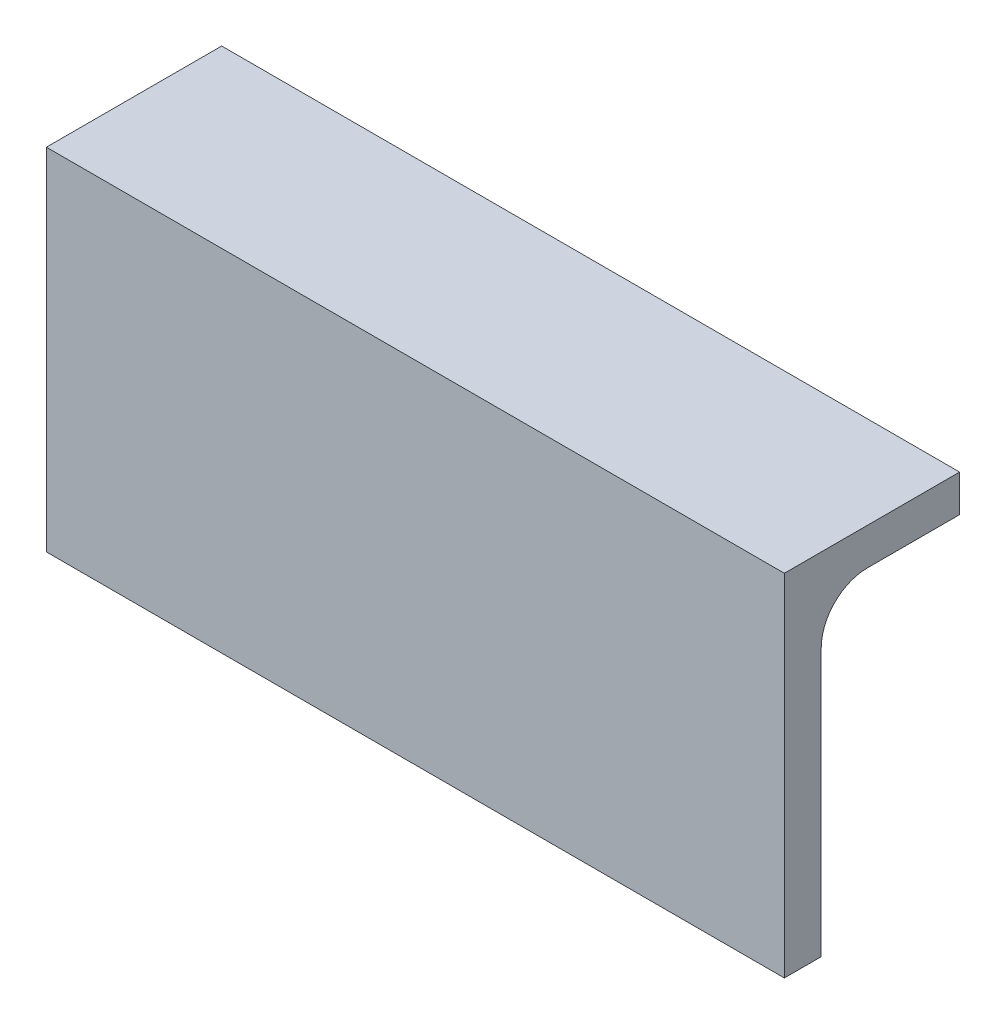
SolidWorks part; units mm, degrees
ref_plane "Front Plane" through (0, 0, 0) normal (0, 0, 1) x (1, 0, 0)
ref_plane "Top Plane" through (0, 0, 0) normal (0, 1, 0) x (1, 0, 0)
ref_plane "Right Plane" through (0, 0, 0) normal (1, 0, 0) x (0, 0, -1)
sketch "Sketch4" plane through (0, 0, 0) normal (0, 0, 1) x (1, 0, 0)
  line L1 (0, 0) -> (32, 0)
  line L2 (0, 0) -> (0, -16)
  line L3 (0, -16) -> (32, -16)
  line L4 (32, 0) -> (32, -16)
  dimension "D1" = 32
  dimension "D2" = 16
extrude "Boss-Extrude3" add sketch "Sketch4" along normal blind 1.6
sketch "Sketch5" plane through (0, 0, 0) normal (0, 0, -1) x (-1, 0, 0)
  line L1 (0, 0) -> (0, -16) construction
  line L2 (-32, 0) -> (0, 0)
  line L3 (-32, 0) -> (-32, -2.4)
  line L4 (-32, -2.4) -> (0, -2.4)
  line L6 (0, 0) -> (0, -2.4)
  dimension "D1" = 2.4
extrude "Boss-Extrude4" add sketch "Sketch5" along normal blind 6
sketch "Sketch6" plane through (0, 0, 0) normal (0, 1, 0) x (1, 0, 0)
  line L0 (0.8, -0.8) -> (0.8, 5.2)
  line L1 (0, -1.6) -> (32, -1.6)
  line L2 (0, -1.6) -> (0, 6)
  line L3 (0, 6) -> (32, 6)
  line L4 (32, -1.6) -> (32, 6)
  line L5 (0.8, 5.2) -> (31.2, 5.2)
  line L6 (31.2, -0.8) -> (31.2, 5.2)
  line L7 (0.8, -0.8) -> (31.2, -0.8)
  dimension "D1" = 0.8
extrude "Boss-Extrude5" add sketch "Sketch6" along normal blind 4.8
sketch "Sketch7" plane through (0, 4.8, 0) normal (0, 1, 0) x (1, 0, 0)
  line L0 (0, -1.6) -> (32, -1.6) construction
  line L1 (10, -1.6) -> (22, -1.6)
  line L2 (10, -1.6) -> (10, -0.8)
  line L3 (10, -0.8) -> (22, -0.8)
  line L4 (22, -1.6) -> (22, -0.8)
  line L5 (0.8, -0.8) -> (31.2, -0.8) construction
  line L6 (31.2, 5.2) -> (0.8, 5.2) construction
  point P8 (16, -1.6)
  point P11 (16, 5.2)
  dimension "D1" = 0
  dimension "D2" = 12
extrude "Cut-Extrude1" cut sketch "Sketch7" against normal blind 4.8
sketch "Sketch8" plane through (0, 0, 1.6) normal (0, 0, 1) x (1, 0, 0)
  line L1 (10, 0) -> (36, 0)
  line L2 (10, 0) -> (10, -0.8)
  line L3 (10, -0.8) -> (36, -0.8)
  line L4 (36, 0) -> (36, -0.8)
  dimension "D1" = 0.8
extrude "Boss-Extrude6" add sketch "Sketch8" along normal blind 12
sketch "Sketch9" plane through (0, 0, 0) normal (0, 1, 0) x (1, 0, 0)
  line L1 (10, -13.6) -> (10.8, -13.6)
  line L2 (10, -13.6) -> (10, -0.8)
  line L3 (10, -0.8) -> (10.8, -0.8)
  line L4 (10.8, -13.6) -> (10.8, -0.8)
  line L5 (36, -13.6) -> (35.2, -13.6)
  line L6 (36, -13.6) -> (36, -0.8)
  line L7 (36, -0.8) -> (35.2, -0.8)
  line L8 (35.2, -13.6) -> (35.2, -0.8)
  dimension "D1" = 0.8
  dimension "D2" = 0.8
  dimension "D3" = 0
  dimension "D4" = 0
extrude "Boss-Extrude7" add sketch "Sketch9" along normal blind 4.8
sketch "Sketch10" plane through (0, 4.8, 0) normal (0, 1, 0) x (1, 0, 0)
  line L1 (-5.9048, 20.3079) -> (68.772, 20.3079)
  line L2 (-5.9048, 20.3079) -> (-5.9048, -25.3109)
  line L3 (-5.9048, -25.3109) -> (68.772, -25.3109)
  line L4 (68.772, 20.3079) -> (68.772, -25.3109)
extrude "Cut-Extrude2" cut sketch "Sketch10" against normal blind 5.6
fillet "Fillet1" radius 2 1 edges at (16, -2.4, 0)
